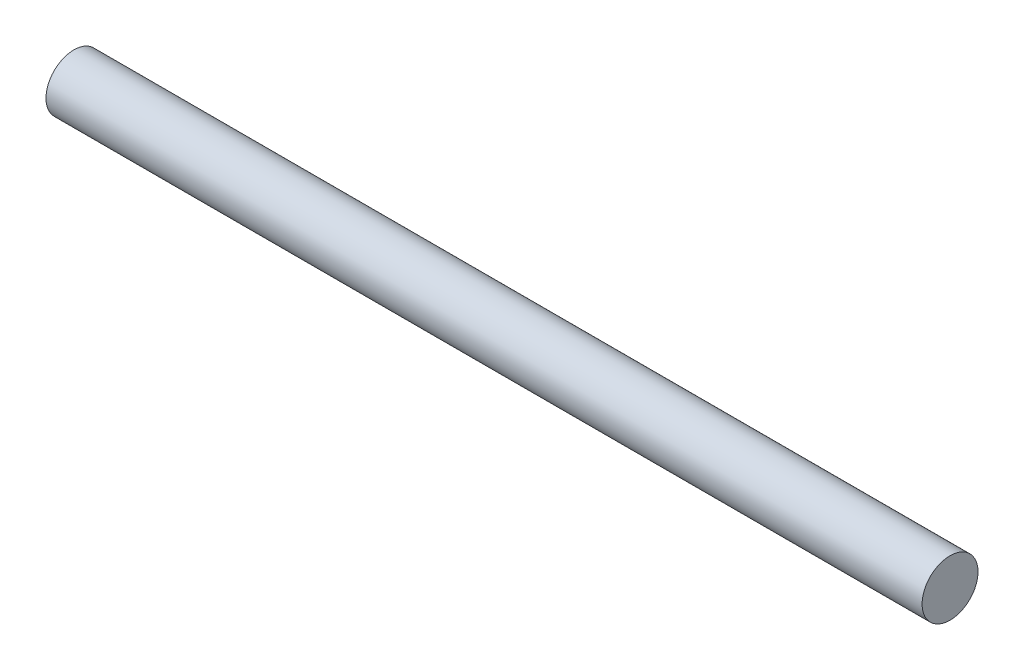
SolidWorks part; units mm, degrees
ref_plane "Front Plane" through (0, 0, 0) normal (0, 0, 1) x (1, 0, 0)
ref_plane "Top Plane" through (0, 0, 0) normal (0, 1, 0) x (1, 0, 0)
ref_plane "Right Plane" through (0, 0, 0) normal (1, 0, 0) x (0, 0, -1)
sketch "Sketch1" plane through (0, 0, 0) normal (1, 0, 0) x (0, 0, -1)
  circle A0 centre (0, 0) radius 1.5
  dimension "D1" = 3
extrude "Boss-Extrude1" add sketch "Sketch1" along normal blind 47
